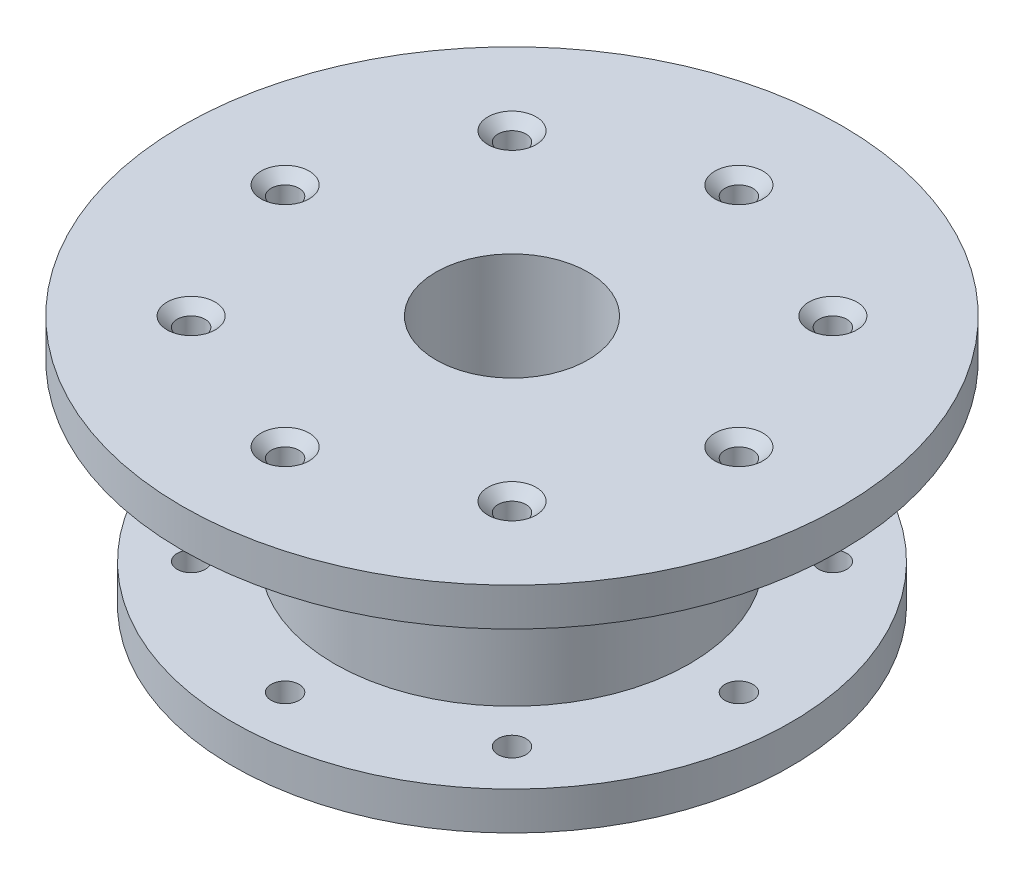
SolidWorks part; units mm, degrees
ref_plane "Front Plane" through (0, 0, 0) normal (0, 0, 1) x (1, 0, 0)
ref_plane "Top Plane" through (0, 0, 0) normal (0, 1, 0) x (1, 0, 0)
ref_plane "Right Plane" through (0, 0, 0) normal (1, 0, 0) x (0, 0, -1)
sketch "Sketch1" plane through (0, 0, 0) normal (0, 0, 1) x (1, 0, 0)
  line L0 (13.1062, 42.0256) -> (113.1062, 42.0256)
  line L1 (113.1062, 42.0256) -> (113.1062, 27.0256)
  line L2 (113.1062, 27.0256) -> (53.1062, 27.0256)
  line L3 (53.1062, 27.0256) -> (53.1062, -41.7604)
  line L4 (53.1062, -41.7604) -> (93.1062, -41.7604)
  line L5 (93.1062, -41.7604) -> (93.1062, -56.7604)
  line L8 (13.1062, 42.0256) -> (13.1062, -56.7604)
  line L9 (-139.9566, -14.3179) -> (133.1432, -14.3179) construction
  line L10 (13.1062, -56.7604) -> (93.1062, -56.7604)
  line L11 (-16.8938, 54.0056) -> (-16.8938, -90.0651) construction
  dimension "D1" = 100
  dimension "D2" = 15
  dimension "D3" = 15
  dimension "D4" = 40
  dimension "D5" = 30
  dimension "D6" = 220
revolve "Revolve2" add sketch "Sketch1" angle 360 about L11
hole_wizard "CSK for M10 Cross Countersunk Head Screw1" positions "Sketch9" profile "Sketch10" countersink size "M10" standard "AS" end condition through all
sketch "Sketch9" plane through (0, 42.0256, 0) normal (0, 1, 0) x (1, 0, 0)
  point P0 (72.5665, 0)
sketch "Sketch10" plane through (72.5665, 42.0256, 0) normal (1, 0, 0) x (0, 0, 1)
  line L0 (0, 0) -> (0, 98.786)
  line L1 (0, 98.786) -> (5.5, 98.786)
  line L2 (5.5, 98.786) -> (5.5, 3.8628)
  line L3 (5.5, 3.8628) -> (9.5, 0)
  line L5 (9.5, 0) -> (0, 0)
  line L6 (-5.5, 3.8628) -> (-9.5, 0) construction
  line L11 (0, -6.35) -> (0, 107.95) construction
  dimension "Thru Hole Dia." = 11
  dimension "Thru Hole Depth" = 98.786
  dimension "Near C'Sink Dia." = 19
  dimension "Near C'Sink Angle" = 92
pattern_circular "CirPattern2" count 8 every 45 about axis through (-16.8938, 0, 0) along (0, 1, 0) of "CSK for M10 Cross Countersunk Head Screw1"
